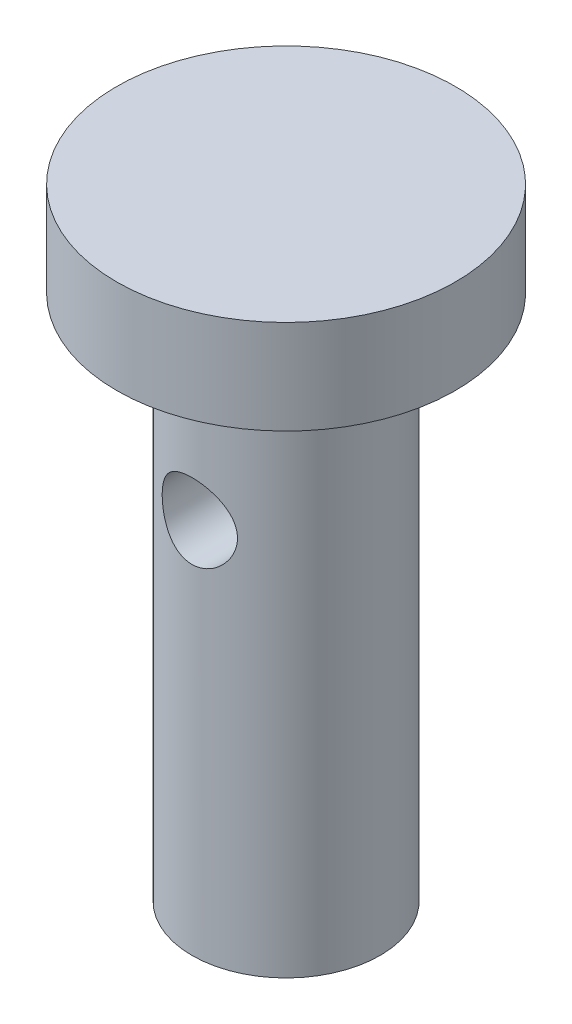
SolidWorks part; units mm, degrees
ref_plane "Alzado" through (0, 0, 0) normal (0, 0, 1) x (1, 0, 0)
ref_plane "Planta" through (0, 0, 0) normal (0, 1, 0) x (1, 0, 0)
ref_plane "Vista lateral" through (0, 0, 0) normal (1, 0, 0) x (0, 0, -1)
sketch "Croquis1" plane through (0, 0, 0) normal (0, 1, 0) x (1, 0, 0)
  circle A0 centre (0, 0) radius 2.5
  dimension "D1" = 5
extrude "Saliente-Extruir1" add sketch "Croquis1" along normal blind 14
sketch "Croquis2" plane through (0, 14, 0) normal (0, 1, 0) x (1, 0, 0)
  circle A0 centre (0, 0) radius 4.5
  dimension "D1" = 9
extrude "Saliente-Extruir2" add sketch "Croquis2" along normal blind 2.5
sketch "Croquis3" plane through (0, 0, 0) normal (0, 0, 1) x (1, 0, 0)
  line L0 (0, 14) -> (0, 9) construction
  line L1 (-2.5, 14) -> (2.5, 14) construction
  circle A0 centre (0, 10) radius 1
  dimension "D1" = 5
  dimension "D2" = 2
extrude "Cortar-Extruir1" cut sketch "Croquis3" against normal mid plane 6
